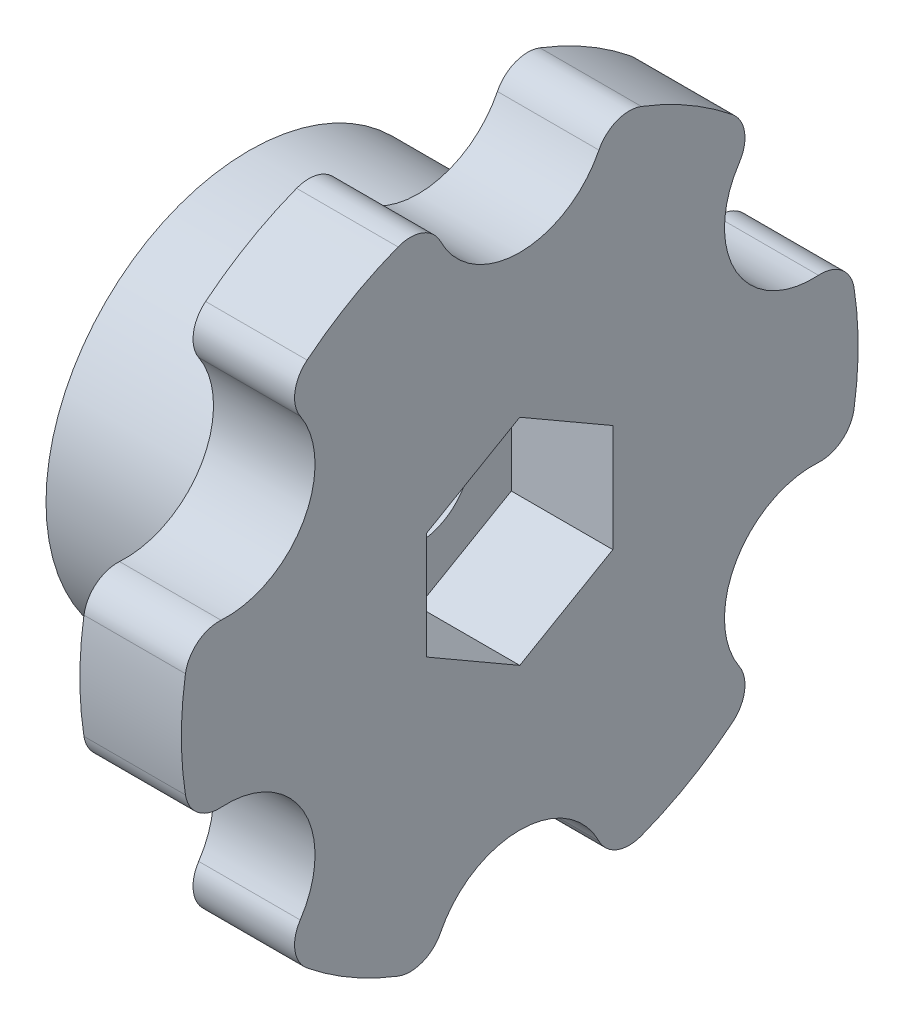
SolidWorks part; units mm, degrees
ref_plane "Front Plane" through (0, 0, 0) normal (0, 0, 1) x (1, 0, 0)
ref_plane "Top Plane" through (0, 0, 0) normal (0, 1, 0) x (1, 0, 0)
ref_plane "Right Plane" through (0, 0, 0) normal (1, 0, 0) x (0, 0, -1)
sketch "Sketch2" plane through (0, 0, 0) normal (0, 0, 1) x (1, 0, 0)
  line L0 (0, 0) -> (8, 0)
  line L1 (8, 0) -> (8, 10)
  line L2 (8, 10) -> (5, 10)
  line L3 (5, 10) -> (5, 6)
  line L4 (5, 6) -> (0, 6)
  line L5 (0, 6) -> (0, 0)
  dimension "D1" = 6
  dimension "D2" = 8
  dimension "D3" = 5
  dimension "D4" = 10
revolve "Revolve1" add sketch "Sketch2" angle 360 about L0
sketch "Sketch3" plane through (0, 0, 0) normal (-1, 0, 0) x (0, 0, 1)
  circle A0 centre (0, 0) radius 1.55
  dimension "D1" = 3.1
extrude "Cut-Extrude1" cut sketch "Sketch3" against normal through all
sketch "Sketch4" plane through (8, 0, 0) normal (1, 0, 0) x (0, 0, -1)
  line L0 (0, 0) -> (0, 10) construction
  line L1 (0, 0) -> (5, 8.6603) construction
  line L2 (0, 0) -> (2.5882, 9.6593) construction
  line L3 (0, 0) -> (8.6603, 5) construction
  circle A0 centre (0, 0) radius 10 construction
  circle A1 centre (0, 10) radius 2.6105
  circle A3 centre (8.6603, 5) radius 2.6105
  circle A4 centre (8.6603, -5) radius 2.6105
  circle A5 centre (0, -10) radius 2.6105
  circle A6 centre (-8.6603, -5) radius 2.6105
  circle A7 centre (-8.6603, 5) radius 2.6105
  point P21 (0, 0)
  dimension "D3" = 6
  dimension "D5" = 8.6603
  dimension "D1" = 30
  dimension "D2" = 15
  dimension "D4" = 60
extrude "Cut-Extrude2" cut sketch "Sketch4" against normal through all
fillet "Fillet1" radius 1 12 edges at (6.5, 9.6593, 2.5882) (6.5, 9.6593, -2.5882) (6.5, 2.5882, 9.6593) (6.5, 7.0711, 7.0711) (6.5, -7.0711, 7.0711) (6.5, -2.5882, 9.6593) (6.5, -9.6593, -2.5882) (6.5, -9.6593, 2.5882) (6.5, -2.5882, -9.6593) (6.5, -7.0711, -7.0711) (6.5, 7.0711, -7.0711) (6.5, 2.5882, -9.6593)
sketch "Sketch5" plane through (8, 0, 0) normal (1, 0, 0) x (0, 0, -1)
  line L0 (0, 0) -> (5, 0) construction
  line L1 (0, 0) -> (2.7496, 1.5875) construction
  line L2 (2.7496, 1.5875) -> (0, 3.175)
  line L3 (0, 3.175) -> (-2.7496, 1.5875)
  line L4 (-2.7496, 1.5875) -> (-2.7496, -1.5875)
  line L5 (-2.7496, -1.5875) -> (0, -3.175)
  line L6 (0, -3.175) -> (2.7496, -1.5875)
  line L7 (2.7496, -1.5875) -> (2.7496, 1.5875)
  circle A0 centre (0, 0) radius 3.175 construction
  dimension "D2" = 6.35
  dimension "D1" = 5
  dimension "D3" = 30
extrude "Cut-Extrude3" cut sketch "Sketch5" against normal blind 3
